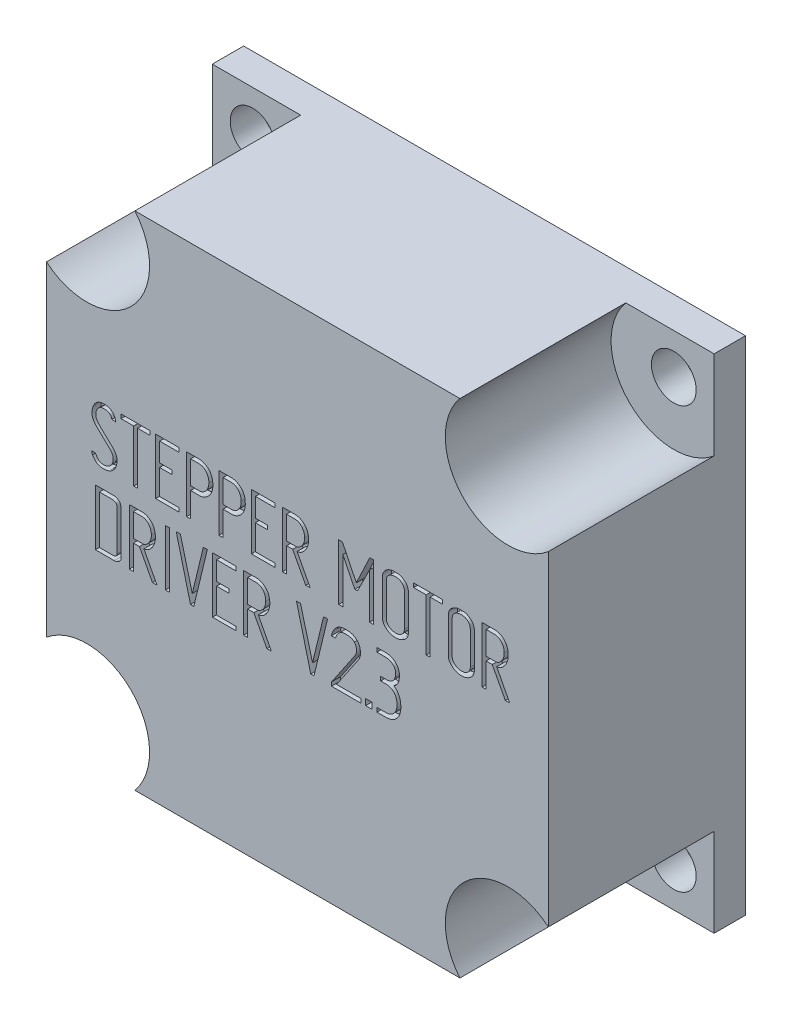
SolidWorks part; units mm, degrees
ref_plane "Front Plane" through (0, 0, 0) normal (0, 0, 1) x (1, 0, 0)
ref_plane "Top Plane" through (0, 0, 0) normal (0, 1, 0) x (1, 0, 0)
ref_plane "Right Plane" through (0, 0, 0) normal (1, 0, 0) x (0, 0, -1)
ref_plane "Plane1" through (0, 0, 22) normal (0, 0, 1) x (1, 0, 0)
sketch "Sketch1" plane through (0, 0, 22) normal (0, 0, 1) x (1, 0, 0)
  line L0 (-22.094, 7.6151) -> (-22.094, -6.9533)
  line L1 (-20.4497, -6.9533) -> (28, -6.9533)
  line L2 (28, -6.9533) -> (28, 7.6151)
  line L3 (28, 7.6151) -> (-22.094, 7.6151)
  line L4 (-11.9113, 4.083) -> (-11.9113, 7.5989)
  line L5 (-8.2986, 4.083) -> (-8.2986, 7.5989)
  line L6 (-0.0334, 4.1265) -> (1.4223, 1.3505)
  line L7 (1.4223, 1.3505) -> (0.9242, 1.3505)
  line L8 (0.9242, 1.3505) -> (-0.5316, 4.0975)
  line L9 (-0.5316, 4.0975) -> (-1.6681, 4.0975)
  line L10 (-1.6681, 4.0975) -> (-1.6681, 7.5989)
  spline S0 degree 3 poles (-20.4497, -6.9533) (-20.9978, -6.9533) (-21.5459, -6.9533) (-22.094, -6.9533) knots 0.061126 0.061126 0.061126 0.061126 0.154392 0.154392 0.154392 0.154392
  spline S1 degree 3 poles (-9.4351, 5.8531) (-9.4351, 6.6849) (-9.7673, 7.2304) (-10.4362, 7.4877) (-10.6248, 7.5603) (-10.7989, 7.5989) (-10.9488, 7.5989) (-11.2696, 7.5989) (-11.5904, 7.5989) (-11.9113, 7.5989) knots 0.764873 0.764873 0.764873 0.764873 0.88574 0.88574 0.88574 0.916733 0.916733 0.916733 0.973286 0.973286 0.973286 0.973286
  spline S2 degree 3 poles (-11.9113, 4.083) (-11.584, 4.083) (-11.2567, 4.0786) (-10.9295, 4.083) (-10.5716, 4.0878) (-10.2488, 4.2344) (-9.9526, 4.5183) (-9.6044, 4.852) (-9.4351, 5.2969) (-9.4351, 5.8531) knots 0 0 0 0 0.057691 0.057691 0.057691 0.122121 0.122121 0.122121 0.208716 0.208716 0.208716 0.208716
  spline S3 degree 3 poles (-5.8176, 5.8531) (-5.8176, 6.6849) (-6.1546, 7.2304) (-6.8235, 7.4877) (-7.0121, 7.5603) (-7.1814, 7.5989) (-7.3362, 7.5989) (-7.657, 7.5989) (-7.9778, 7.5989) (-8.2986, 7.5989) knots 0.764782 0.764782 0.764782 0.764782 0.885765 0.885765 0.885765 0.916754 0.916754 0.916754 0.973293 0.973293 0.973293 0.973293
  spline S4 degree 3 poles (-8.2986, 4.083) (-7.9713, 4.083) (-7.644, 4.0786) (-7.3168, 4.083) (-6.9589, 4.0878) (-6.6361, 4.2344) (-6.3399, 4.5183) (-5.9917, 4.852) (-5.8176, 5.2969) (-5.8176, 5.8531) knots 0 0 0 0 0.057676 0.057676 0.057676 0.12209 0.12209 0.12209 0.208766 0.208766 0.208766 0.208766
  spline S5 degree 3 poles (-0.0334, 4.1265) (0.3438, 4.1797) (0.6607, 4.3892) (0.9097, 4.7601) (1.137, 5.0986) (1.2482, 5.471) (1.2482, 6.6849) (0.9187, 7.2141) (0.2713, 7.4974) (0.1165, 7.5651) (-0.0431, 7.5989) (-0.2075, 7.5989) (-0.6944, 7.5989) (-1.1812, 7.5989) (-1.6681, 7.5989) knots 0.592094 0.592094 0.592094 0.592094 0.642618 0.642618 0.642618 0.688837 0.688837 0.780724 0.780724 0.780724 0.80197 0.80197 0.80197 0.864914 0.864914 0.864914 0.864914
extrude "Boss-Extrude1" add sketch "Sketch1" against normal blind 1
sketch "Sketch2" plane through (-22.094, 0, 0) normal (-1, 0, 0) x (0, 0, 1)
  line L0 (21, 7.6151) -> (22, 7.6151)
  line L1 (22, 7.6151) -> (22, -6.9533)
  line L2 (22, -6.9533) -> (21, -6.9533)
  line L3 (21, -6.9533) -> (21, 7.6151)
extrude "Boss-Extrude2" add sketch "Sketch2" along normal blind 5.906
sketch "Sketch3" plane through (0, 0, 21) normal (0, 0, -1) x (-1, 0, 0)
  line L0 (-28, -6.9533) -> (-28, 7.6151)
  line L1 (-28, 7.6151) -> (28, 7.6151)
  line L2 (28, 7.6151) -> (28, -6.9533)
  line L3 (28, -6.9533) -> (-28, -6.9533)
extrude "Boss-Extrude3" add sketch "Sketch3" along normal blind 21
sketch "Sketch4" plane through (0, 0, 22) normal (0, 0, 1) x (1, 0, 0)
  line L0 (8.8629, -0.6904) -> (8.8629, -1.145)
  line L1 (9.2885, -3.2681) -> (9.2885, -3.7227)
  line L2 (8.8725, -6.4842) -> (8.8725, -6.9388)
  spline S0 degree 3 poles (8.8629, -0.6904) (9.1676, -0.6904) (9.4722, -0.6904) (9.7769, -0.6904) (10.4685, -0.6904) (10.9521, -0.9516) (11.2181, -1.4739) (11.3271, -1.6878) (11.3826, -1.8849) (11.3826, -2.3541) (11.3535, -2.591) (11.3003, -2.77) (11.2167, -3.0515) (11.0295, -3.2826) (10.749, -3.4761) knots 0.699691 0.699691 0.699691 0.699691 0.739881 0.739881 0.739881 0.816228 0.816228 0.816228 0.839159 0.839159 0.874762 0.874762 0.874762 0.914947 0.914947 0.914947 0.914947
  spline S1 degree 3 poles (9.2885, -3.2681) (9.5045, -3.2681) (9.7205, -3.2681) (9.9365, -3.2681) (10.3089, -3.2681) (10.5942, -3.1182) (10.8022, -2.8135) (10.865, -2.7215) (10.9086, -2.6104) (10.928, -2.4895) (10.9374, -2.4306) (10.9473, -2.2912) (10.9473, -1.8076) (10.8216, -1.5754) (10.5701, -1.3917) (10.3499, -1.2307) (10.0961, -1.145) (9.8011, -1.145) (9.4884, -1.145) (9.1756, -1.145) (8.8629, -1.145) knots 0.459525 0.459525 0.459525 0.459525 0.488019 0.488019 0.488019 0.532951 0.532951 0.532951 0.548357 0.548357 0.548357 0.5721 0.5721 0.60232 0.60232 0.60232 0.638466 0.638466 0.638466 0.679703 0.679703 0.679703 0.679703
  spline S2 degree 3 poles (8.8725, -6.4842) (9.1933, -6.4842) (9.5142, -6.4842) (9.835, -6.4842) (10.2219, -6.4842) (10.5362, -6.3488) (10.7732, -6.0828) (11.0035, -5.8243) (11.1166, -5.4976) (11.1166, -4.7142) (11.0198, -4.3901) (10.8264, -4.1386) (10.6159, -3.865) (10.3186, -3.7227) (9.9317, -3.7227) (9.7173, -3.7227) (9.5029, -3.7227) (9.2885, -3.7227) knots 0.185727 0.185727 0.185727 0.185727 0.228043 0.228043 0.228043 0.274363 0.274363 0.274363 0.320276 0.320276 0.366189 0.366189 0.366189 0.411267 0.411267 0.411267 0.439537 0.439537 0.439537 0.439537
  spline S3 degree 3 poles (11.5422, -5.1301) (11.5422, -5.6621) (11.3922, -6.0925) (11.0972, -6.4214) (10.7883, -6.7657) (10.3766, -6.9388) (9.8543, -6.9388) (9.527, -6.9388) (9.1998, -6.9388) (8.8725, -6.9388) knots 0 0 0 0 0.061468 0.061468 0.061468 0.122594 0.122594 0.122594 0.165739 0.165739 0.165739 0.165739
  spline S4 degree 3 poles (10.749, -3.4761) (11.015, -3.5921) (11.223, -3.8243) (11.368, -4.1773) (11.4834, -4.4581) (11.5422, -4.777) (11.5422, -5.1301) knots 0.914947 0.914947 0.914947 0.914947 0.957143 0.957143 0.957143 1 1 1 1
extrude "Cut-Extrude1" cut sketch "Sketch4" against normal blind 1
sketch "Sketch5" plane through (0, 0, 22) normal (0, 0, 1) x (1, 0, 0)
  line L0 (-5.9989, -0.6904) -> (-5.9989, -4.1918)
  line L1 (-5.9989, -4.1918) -> (-4.8624, -4.1918)
  line L2 (-4.8624, -4.1918) -> (-3.4067, -6.9388)
  line L3 (-3.4067, -6.9388) -> (-2.9086, -6.9388)
  line L4 (-2.9086, -6.9388) -> (-4.3691, -4.1628)
  spline S0 degree 3 poles (-5.9989, -0.6904) (-5.5121, -0.6904) (-5.0252, -0.6904) (-4.5384, -0.6904) (-4.3788, -0.6904) (-4.2144, -0.7242) (-4.0596, -0.792) (-3.4121, -1.0752) (-3.0827, -1.6044) (-3.0827, -2.8183) (-3.1939, -3.1907) (-3.4212, -3.5293) (-3.6695, -3.899) (-3.9871, -4.1096) (-4.3691, -4.1628) knots 0.591928 0.591928 0.591928 0.591928 0.654854 0.654854 0.654854 0.67609 0.67609 0.67609 0.767952 0.767952 0.814158 0.814158 0.814158 0.864855 0.864855 0.864855 0.864855
extrude "Cut-Extrude2" cut sketch "Sketch5" against normal blind 1
sketch "Sketch6" plane through (0, 0, 21) normal (0, 0, 1) x (1, 0, 0)
  line L0 (-5.5492, -3.7372) -> (-5.5492, -1.145)
  spline S0 degree 3 poles (-5.5492, -3.7372) (-5.1977, -3.7372) (-4.8463, -3.7372) (-4.4949, -3.7372) (-4.2966, -3.7372) (-4.0983, -3.6308) (-3.9, -3.4132) (-3.6627, -3.1528) (-3.5373, -2.8232) (-3.5373, -2.4169) knots 0.655267 0.655267 0.655267 0.655267 0.783334 0.783334 0.783334 0.868074 0.868074 0.868074 1 1 1 1
  spline S1 degree 3 poles (-3.5373, -2.4169) (-3.5373, -2.0204) (-3.6534, -1.6963) (-3.8903, -1.4497) (-4.087, -1.245) (-4.3159, -1.145) (-4.5722, -1.145) (-4.8979, -1.145) (-5.2235, -1.145) (-5.5492, -1.145) knots 0 0 0 0 0.128337 0.128337 0.128337 0.22169 0.22169 0.22169 0.340387 0.340387 0.340387 0.340387
extrude "Boss-Extrude4" add sketch "Sketch6" along normal blind 1
sketch "Sketch7" plane through (0, 0, 22) normal (0, 0, 1) x (1, 0, 0)
  line L0 (-18.7666, -0.6904) -> (-18.7666, -4.1918)
  line L1 (-18.7666, -4.1918) -> (-17.6301, -4.1918)
  line L2 (-17.6301, -4.1918) -> (-16.1744, -6.9388)
  line L3 (-16.1744, -6.9388) -> (-15.6763, -6.9388)
  line L4 (-15.6763, -6.9388) -> (-17.132, -4.1628)
  spline S0 degree 3 poles (-18.7666, -0.6904) (-18.2798, -0.6904) (-17.7929, -0.6904) (-17.3061, -0.6904) (-17.1417, -0.6904) (-16.9821, -0.7242) (-16.8225, -0.792) (-16.1759, -1.0663) (-15.8504, -1.6044) (-15.8504, -2.8183) (-15.9616, -3.1907) (-16.1889, -3.5293) (-16.4357, -3.8968) (-16.7499, -4.1096) (-17.132, -4.1628) knots 0.591995 0.591995 0.591995 0.591995 0.654928 0.654928 0.654928 0.676368 0.676368 0.676368 0.768214 0.768214 0.814412 0.814412 0.814412 0.864937 0.864937 0.864937 0.864937
extrude "Cut-Extrude3" cut sketch "Sketch7" against normal blind 1
sketch "Sketch8" plane through (0, 0, 21) normal (0, 0, 1) x (1, 0, 0)
  line L0 (-18.312, -3.7372) -> (-18.312, -1.145)
  spline S0 degree 3 poles (-18.312, -3.7372) (-17.9606, -3.7372) (-17.6092, -3.7372) (-17.2577, -3.7372) (-17.0643, -3.7372) (-16.866, -3.6308) (-16.6677, -3.4132) (-16.4282, -3.1504) (-16.3002, -2.8232) (-16.3002, -2.4169) knots 0.655365 0.655365 0.655365 0.655365 0.78352 0.78352 0.78352 0.867758 0.867758 0.867758 1 1 1 1
  spline S1 degree 3 poles (-16.3002, -2.4169) (-16.3002, -2.0204) (-16.4211, -1.6963) (-16.658, -1.4497) (-16.8524, -1.2474) (-17.0788, -1.145) (-17.3351, -1.145) (-17.6608, -1.145) (-17.9864, -1.145) (-18.312, -1.145) knots 0 0 0 0 0.128628 0.128628 0.128628 0.221536 0.221536 0.221536 0.340269 0.340269 0.340269 0.340269
extrude "Boss-Extrude5" add sketch "Sketch8" along normal blind 1
sketch "Sketch9" plane through (0, 0, 22) normal (0, 0, 1) x (1, 0, 0)
  line L0 (-22.094, -6.5132) -> (-22.094, -6.9533)
  line L1 (-22.094, -0.6904) -> (-22.094, -1.145)
  spline S0 degree 3 poles (-20.4497, -6.9533) (-20.9978, -6.9533) (-21.5459, -6.9533) (-22.094, -6.9533) knots 0.061126 0.061126 0.061126 0.061126 0.154392 0.154392 0.154392 0.154392
  spline S1 degree 3 poles (-19.6855, -6.3488) (-19.6855, -6.5326) (-19.7726, -6.6777) (-19.9419, -6.7937) (-20.0935, -6.8977) (-20.261, -6.9533) (-20.4497, -6.9533) knots 0 0 0 0 0.03043 0.03043 0.03043 0.061126 0.061126 0.061126 0.061126
  spline S2 degree 3 poles (-20.2562, -0.7339) (-19.879, -0.8355) (-19.6855, -1.087) (-19.6855, -1.4932) (-19.6855, -3.1117) (-19.6855, -4.7303) (-19.6855, -6.3488) knots 0.665783 0.665783 0.665783 0.665783 0.724543 0.724543 0.724543 1 1 1 1
  spline S3 degree 3 poles (-22.094, -0.6904) (-21.6168, -0.6904) (-21.1396, -0.6904) (-20.6625, -0.6904) (-20.4497, -0.6904) (-20.3142, -0.7049) (-20.2562, -0.7339) knots 0.561263 0.561263 0.561263 0.561263 0.642474 0.642474 0.642474 0.665783 0.665783 0.665783 0.665783
  spline S4 degree 3 poles (-20.1401, -6.1554) (-20.1401, -4.6497) (-20.1401, -3.144) (-20.1401, -1.6383) (-20.1401, -1.3094) (-20.3142, -1.145) (-20.6673, -1.145) (-21.1429, -1.145) (-21.6184, -1.145) (-22.094, -1.145) knots 0 0 0 0 0.315993 0.315993 0.315993 0.37397 0.37397 0.37397 0.473775 0.473775 0.473775 0.473775
  spline S5 degree 3 poles (-22.094, -6.5132) (-21.6104, -6.5132) (-21.1267, -6.5132) (-20.6431, -6.5132) (-20.3094, -6.5132) (-20.1401, -6.3972) (-20.1401, -6.1554) knots 0.849313 0.849313 0.849313 0.849313 0.95081 0.95081 0.95081 1 1 1 1
extrude "Cut-Extrude4" cut sketch "Sketch9" against normal blind 1
sketch "Sketch10" plane through (0, 0, 22) normal (0, 0, 1) x (1, 0, 0)
  line L0 (20.6029, 7.5989) -> (20.6029, 4.0975)
  line L1 (20.6029, 4.0975) -> (21.7394, 4.0975)
  line L2 (21.7394, 4.0975) -> (23.1999, 1.3505)
  line L3 (23.1999, 1.3505) -> (23.6932, 1.3505)
  line L4 (23.6932, 1.3505) -> (22.2375, 4.1265)
  spline S0 degree 3 poles (20.6029, 7.5989) (21.0913, 7.5989) (21.5798, 7.5989) (22.0683, 7.5989) (22.2279, 7.5989) (22.3875, 7.5651) (22.547, 7.4974) (23.1977, 7.2213) (23.524, 6.6849) (23.524, 5.471) (23.4079, 5.0986) (23.1854, 4.7601) (22.9387, 4.3846) (22.6196, 4.1797) (22.2375, 4.1265) knots 0.591753 0.591753 0.591753 0.591753 0.65488 0.65488 0.65488 0.676109 0.676109 0.676109 0.768003 0.768003 0.814226 0.814226 0.814226 0.864967 0.864967 0.864967 0.864967
extrude "Cut-Extrude5" cut sketch "Sketch10" against normal blind 1
sketch "Sketch11" plane through (0, 0, 21) normal (0, 0, 1) x (1, 0, 0)
  line L0 (21.0575, 4.5521) -> (21.0575, 7.1443)
  spline S0 degree 3 poles (21.0575, 4.5521) (21.4089, 4.5521) (21.7604, 4.5521) (22.1118, 4.5521) (22.3052, 4.5521) (22.5035, 4.6585) (22.7066, 4.8761) (22.9471, 5.1337) (23.0694, 5.4662) (23.0694, 5.8724) knots 0.655176 0.655176 0.655176 0.655176 0.783281 0.783281 0.783281 0.867942 0.867942 0.867942 1 1 1 1
  spline S1 degree 3 poles (23.0694, 5.8724) (23.0694, 6.269) (22.9533, 6.5882) (22.7163, 6.8348) (22.5172, 7.042) (22.2907, 7.1443) (22.0344, 7.1443) (21.7088, 7.1443) (21.3831, 7.1443) (21.0575, 7.1443) knots 0 0 0 0 0.127832 0.127832 0.127832 0.221516 0.221516 0.221516 0.340204 0.340204 0.340204 0.340204
extrude "Boss-Extrude6" add sketch "Sketch11" along normal blind 1
sketch "Sketch12" plane through (0, 0, 22) normal (0, 0, 1) x (1, 0, 0)
  line L0 (18.625, 7.6151) -> (17.9743, 7.6151)
  spline S0 degree 3 poles (18.625, 7.6151) (18.8668, 7.5692) (19.0854, 7.4665) (19.2826, 7.3136) (19.5875, 7.077) (19.742, 6.7768) (19.742, 6.4189) (19.742, 5.1163) (19.742, 3.8138) (19.742, 2.5112) (19.742, 2.1485) (19.5873, 1.8486) (19.2826, 1.6165) (19.0002, 1.4013) (18.678, 1.2925) (17.9333, 1.2925) (17.6044, 1.3989) (17.3142, 1.6213) (16.9964, 1.865) (16.8354, 2.163) (16.8354, 2.5209) (16.8354, 3.8202) (16.8354, 5.1196) (16.8354, 6.4189) (16.8354, 6.8106) (16.9999, 7.125) (17.3239, 7.3571) (17.5103, 7.4907) (17.7263, 7.5751) (17.9743, 7.6151) knots 0.65 0.65 0.65 0.65 0.695442 0.695442 0.695442 0.759666 0.759666 0.759666 1 1 1 1.064284 1.064284 1.064284 1.12926 1.12926 1.194235 1.194235 1.194235 1.259381 1.259381 1.259381 1.499095 1.499095 1.499095 1.566888 1.566888 1.566888 1.611816 1.611816 1.611816 1.611816
extrude "Cut-Extrude6" cut sketch "Sketch12" against normal blind 1
sketch "Sketch13" plane through (0, 0, 22) normal (0, 0, 1) x (1, 0, 0)
  line L0 (11.2693, 7.6151) -> (10.6205, 7.6151)
  spline S0 degree 3 poles (11.2693, 7.6151) (11.5113, 7.5692) (11.731, 7.4665) (11.9315, 7.3136) (12.2384, 7.0795) (12.3861, 6.7768) (12.3861, 6.4189) (12.3861, 5.1163) (12.3861, 3.8138) (12.3861, 2.5112) (12.3861, 2.1485) (12.2362, 1.8486) (11.9315, 1.6165) (11.646, 1.399) (11.3221, 1.2925) (10.5822, 1.2925) (10.2485, 1.3989) (9.9583, 1.6213) (9.6435, 1.8626) (9.4843, 2.163) (9.4843, 2.5209) (9.4843, 3.8202) (9.4843, 5.1196) (9.4843, 6.4189) (9.4843, 6.8106) (9.6439, 7.125) (9.968, 7.3571) (10.1543, 7.4907) (10.3727, 7.5751) (10.6205, 7.6151) knots 0.649922 0.649922 0.649922 0.649922 0.695537 0.695537 0.695537 0.759638 0.759638 0.759638 1 1 1 1.064152 1.064152 1.064152 1.12969 1.12969 1.194377 1.194377 1.194377 1.259336 1.259336 1.259336 1.499071 1.499071 1.499071 1.566736 1.566736 1.566736 1.611656 1.611656 1.611656 1.611656
extrude "Cut-Extrude7" cut sketch "Sketch13" against normal blind 1
sketch "Sketch14" plane through (0, 0, 21) normal (0, 0, 1) x (1, 0, 0)
  spline S0 degree 3 poles (9.9196, 6.3318) (9.9196, 5.0873) (9.9196, 3.8428) (9.9196, 2.5983) (9.9196, 2.3323) (10.0502, 2.1146) (10.3162, 1.9502) (10.5272, 1.8197) (10.7466, 1.7471) (11.2012, 1.7471) (11.414, 1.8099) (11.6026, 1.9454) (11.8227, 2.1034) (11.9315, 2.3178) (11.9315, 2.5983) knots 0.500978 0.500978 0.500978 0.500978 0.780719 0.780719 0.780719 0.840435 0.840435 0.840435 0.890577 0.890577 0.942898 0.942898 0.942898 1 1 1 1
  spline S1 degree 3 poles (11.9315, 2.5983) (11.9315, 3.8412) (11.9315, 5.0841) (11.9315, 6.327) (11.9315, 6.5833) (11.8347, 6.7961) (11.6413, 6.9557) (11.456, 7.1086) (11.2351, 7.1879) (10.7224, 7.1879) (10.5048, 7.1298) (10.3162, 7.0186) (10.0526, 6.8631) (9.9196, 6.6317) (9.9196, 6.3318) knots 0 0 0 0 0.279319 0.279319 0.279319 0.333033 0.333033 0.333033 0.387798 0.387798 0.43858 0.43858 0.43858 0.500978 0.500978 0.500978 0.500978
extrude "Boss-Extrude7" add sketch "Sketch14" along normal blind 1
sketch "Sketch15" plane through (0, 0, 22) normal (0, 0, 1) x (1, 0, 0)
  line L0 (-20.7132, 6.5495) -> (-20.2635, 6.5495)
  line L1 (-20.2635, 6.5495) -> (-20.336, 6.83)
  line L2 (-22.551, 2.4) -> (-22.9766, 2.4)
  line L3 (-22.9766, 2.4) -> (-22.8654, 2.0518)
  spline S0 degree 3 poles (-20.128, 2.8884) (-20.128, 3.2705) (-20.3383, 3.6502) (-20.7471, 4.0346) (-21.1259, 4.3909) (-21.5048, 4.7472) (-21.8836, 5.1034) (-22.2899, 5.4855) (-22.4978, 5.8144) (-22.4978, 6.3899) (-22.4282, 6.6475) (-22.2753, 6.8397) (-22.1061, 7.0524) (-21.8739, 7.1588) (-21.0711, 7.1588) (-20.7809, 6.9557) (-20.7132, 6.5495) knots 0.706165 0.706165 0.706165 0.706165 0.763602 0.763602 0.763602 0.830481 0.830481 0.830481 0.869878 0.869878 0.91572 0.91572 0.91572 0.946691 0.946691 1 1 1 1
  spline S1 degree 3 poles (-20.336, 6.83) (-20.5391, 7.3523) (-20.955, 7.6135) (-22.0239, 7.6135) (-22.3638, 7.4549) (-22.5994, 7.1443) (-22.8122, 6.8638) (-22.9234, 6.4963) (-22.9234, 5.6741) (-22.7213, 5.3007) (-22.314, 4.9197) (-21.9384, 4.5682) (-21.5701, 4.2087) (-21.1872, 3.8654) (-20.7664, 3.4881) (-20.5536, 3.1448) (-20.5536, 2.5064) (-20.6601, 2.2451) (-20.8632, 2.0324) (-21.0663, 1.8196) (-21.3274, 1.7181) (-21.9078, 1.7181) (-22.1143, 1.7923) (-22.2608, 1.9502) (-22.3237, 2.0179) (-22.4204, 2.1678) (-22.551, 2.4) knots 0.203882 0.203882 0.203882 0.203882 0.273058 0.273058 0.321481 0.321481 0.321481 0.379716 0.379716 0.427932 0.427932 0.427932 0.494085 0.494085 0.494085 0.539652 0.539652 0.585219 0.585219 0.585219 0.621664 0.621664 0.651483 0.651483 0.651483 0.674464 0.674464 0.674464 0.674464
  spline S2 degree 3 poles (-22.8654, 2.0518) (-22.6719, 1.7858) (-22.541, 1.6266) (-22.4688, 1.5681) (-22.2657, 1.4037) (-21.9948, 1.3215) (-21.1824, 1.3215) (-20.8101, 1.4667) (-20.5391, 1.7519) (-20.2635, 2.0421) (-20.128, 2.4193) (-20.128, 2.8884) knots 0 0 0 0 0.026856 0.026856 0.026856 0.064877 0.064877 0.116822 0.116822 0.116822 0.169968 0.169968 0.169968 0.169968
extrude "Cut-Extrude8" cut sketch "Sketch15" against normal blind 1
sketch "Sketch16" plane through (-8.2986, 0, 0) normal (1, 0, 0) x (0, 0, -1)
  line L0 (-22, 4.083) -> (-21, 4.083)
  line L1 (-21, 4.083) -> (-21, 7.5989)
  line L2 (-21, 7.5989) -> (-22, 7.5989)
  line L3 (-22, 7.5989) -> (-22, 4.083)
extrude "Cut-Extrude9" cut sketch "Sketch16" against normal blind 0.4546
sketch "Sketch17" plane through (-11.9113, 0, 0) normal (1, 0, 0) x (0, 0, -1)
  line L0 (-22, 4.083) -> (-21, 4.083)
  line L1 (-21, 4.083) -> (-21, 7.5989)
  line L2 (-21, 7.5989) -> (-22, 7.5989)
  line L3 (-22, 7.5989) -> (-22, 4.083)
extrude "Cut-Extrude10" cut sketch "Sketch17" against normal blind 0.4546
sketch "Sketch18" plane through (-22.094, 0, 0) normal (1, 0, 0) x (0, 0, -1)
  line L0 (-22, -0.6904) -> (-22, -6.9533)
  line L1 (-22, -6.9533) -> (-21, -6.9533)
  line L2 (-21, -6.9533) -> (-21, -0.6904)
  line L3 (-21, -0.6904) -> (-22, -0.6904)
extrude "Cut-Extrude11" cut sketch "Sketch18" against normal blind 0.4546
sketch "Sketch19" plane through (0, -6.9533, 0) normal (0, -1, 0) x (1, 0, 0)
  line L0 (28, 22) -> (28, 0)
  line L1 (28, 0) -> (-28, 0)
  line L2 (-28, 0) -> (-28, 22)
  line L3 (-28, 22) -> (28, 22)
extrude "Boss-Extrude8" add sketch "Sketch19" along normal blind 21.0467
sketch "Sketch20" plane through (0, 7.6151, 0) normal (0, 1, 0) x (-1, 0, 0)
  line L0 (28, 22) -> (28, 0)
  line L1 (28, 0) -> (-28, 0)
  line L2 (-28, 0) -> (-28, 22)
  line L3 (-28, 22) -> (28, 22)
extrude "Boss-Extrude9" add sketch "Sketch20" along normal blind 20.3849
sketch "Sketch21" plane through (0, 4.083, 0) normal (0, 1, 0) x (-1, 0, 0)
  line L0 (8.7532, 22) -> (8.2986, 22)
  line L1 (8.2986, 22) -> (8.2986, 21)
  line L2 (8.2986, 21) -> (8.7532, 21)
  line L3 (8.7532, 21) -> (8.7532, 22)
extrude "Cut-Extrude12" cut sketch "Sketch21" against normal blind 2.747
sketch "Sketch22" plane through (0, 4.0975, 0) normal (0, 1, 0) x (-1, 0, 0)
  line L0 (1.6681, 22) -> (1.2135, 22)
  line L1 (1.2135, 22) -> (1.2135, 21)
  line L2 (1.2135, 21) -> (1.6681, 21)
  line L3 (1.6681, 21) -> (1.6681, 22)
extrude "Cut-Extrude13" cut sketch "Sketch22" against normal blind 2.747
sketch "Sketch23" plane through (0, 4.0975, 0) normal (0, 1, 0) x (-1, 0, 0)
  line L0 (-20.6029, 22) -> (-21.0575, 22)
  line L1 (-21.0575, 22) -> (-21.0575, 21)
  line L2 (-21.0575, 21) -> (-20.6029, 21)
  line L3 (-20.6029, 21) -> (-20.6029, 22)
extrude "Cut-Extrude14" cut sketch "Sketch23" against normal blind 2.747
sketch "Sketch24" plane through (0, -4.1918, 0) normal (0, 1, 0) x (-1, 0, 0)
  line L0 (18.7666, 22) -> (18.312, 22)
  line L1 (18.312, 22) -> (18.312, 21)
  line L2 (18.312, 21) -> (18.7666, 21)
  line L3 (18.7666, 21) -> (18.7666, 22)
extrude "Cut-Extrude15" cut sketch "Sketch24" against normal blind 2.747
sketch "Sketch25" plane through (0, -4.1918, 0) normal (0, 1, 0) x (-1, 0, 0)
  line L0 (5.9989, 22) -> (5.5492, 22)
  line L1 (5.5492, 22) -> (5.5492, 21)
  line L2 (5.5492, 21) -> (5.9989, 21)
  line L3 (5.9989, 21) -> (5.9989, 22)
extrude "Cut-Extrude16" cut sketch "Sketch25" against normal blind 2.747
sketch "Sketch26" plane through (0, 4.083, 0) normal (0, 1, 0) x (-1, 0, 0)
  line L0 (12.3659, 22) -> (11.9113, 22)
  line L1 (11.9113, 22) -> (11.9113, 21)
  line L2 (11.9113, 21) -> (12.3659, 21)
  line L3 (12.3659, 21) -> (12.3659, 22)
extrude "Cut-Extrude17" cut sketch "Sketch26" against normal blind 2.747
sketch "Sketch27" plane through (0, 0, 21) normal (0, 0, 1) x (1, 0, 0)
  line L0 (-1.2135, 4.5521) -> (-1.2135, 7.1443)
  spline S0 degree 3 poles (-1.2135, 7.1443) (-0.8894, 7.1443) (-0.5654, 7.1443) (-0.2414, 7.1443) (0.0198, 7.1443) (0.2438, 7.0396) (0.4405, 6.8348) (0.6775, 6.5882) (0.7984, 6.269) (0.7984, 5.8724) knots 0 0 0 0 0.118137 0.118137 0.118137 0.211946 0.211946 0.211946 0.340071 0.340071 0.340071 0.340071
  spline S1 degree 3 poles (0.7984, 5.8724) (0.7984, 5.4662) (0.6703, 5.139) (0.4309, 4.8761) (0.2326, 4.6585) (0.0343, 4.5521) (-0.1592, 4.5521) (-0.5106, 4.5521) (-0.862, 4.5521) (-1.2135, 4.5521) knots 0.655262 0.655262 0.655262 0.655262 0.787543 0.787543 0.787543 0.871807 0.871807 0.871807 1 1 1 1
extrude "Boss-Extrude10" add sketch "Sketch27" along normal blind 1
sketch "Sketch28" plane through (0, 0, 21) normal (0, 0, 1) x (1, 0, 0)
  line L0 (-8.2986, 4.5376) -> (-8.2986, 7.1443)
  spline S0 degree 3 poles (-6.2722, 5.8579) (-6.2722, 5.4468) (-6.3987, 5.1139) (-6.6397, 4.8616) (-6.8477, 4.644) (-7.075, 4.5376) (-7.3265, 4.5376) (-7.6505, 4.5376) (-7.9745, 4.5376) (-8.2986, 4.5376) knots 0.655969 0.655969 0.655969 0.655969 0.78778 0.78778 0.78778 0.882375 0.882375 0.882375 1 1 1 1
  spline S1 degree 3 poles (-8.2986, 7.1443) (-7.9891, 7.1443) (-7.6795, 7.1443) (-7.37, 7.1443) (-7.0363, 7.1443) (-6.7689, 7.0062) (-6.5624, 6.7429) (-6.3689, 6.4963) (-6.2722, 6.2013) (-6.2722, 5.8579) knots 0 0 0 0 0.112302 0.112302 0.112302 0.225653 0.225653 0.225653 0.340548 0.340548 0.340548 0.340548
extrude "Boss-Extrude11" add sketch "Sketch28" along normal blind 1
sketch "Sketch29" plane through (0, 0, 21) normal (0, 0, 1) x (1, 0, 0)
  line L0 (-11.9113, 4.5376) -> (-11.9113, 7.1443)
  spline S0 degree 3 poles (-9.8849, 5.8579) (-9.8849, 5.4468) (-10.0114, 5.1139) (-10.2524, 4.8616) (-10.4604, 4.644) (-10.6877, 4.5376) (-10.9392, 4.5376) (-11.2632, 4.5376) (-11.5872, 4.5376) (-11.9113, 4.5376) knots 0.655969 0.655969 0.655969 0.655969 0.78778 0.78778 0.78778 0.882375 0.882375 0.882375 1 1 1 1
  spline S1 degree 3 poles (-11.9113, 7.1443) (-11.6017, 7.1443) (-11.2922, 7.1443) (-10.9827, 7.1443) (-10.649, 7.1443) (-10.3816, 7.0062) (-10.175, 6.7429) (-9.9816, 6.4963) (-9.8849, 6.2013) (-9.8849, 5.8579) knots 0 0 0 0 0.112302 0.112302 0.112302 0.225653 0.225653 0.225653 0.340548 0.340548 0.340548 0.340548
extrude "Boss-Extrude12" add sketch "Sketch29" along normal blind 1
sketch "Sketch30" plane through (0, 0, 21) normal (0, 0, 1) x (1, 0, 0)
  spline S0 degree 3 poles (17.2755, 6.3318) (17.2755, 5.0873) (17.2755, 3.8428) (17.2755, 2.5983) (17.2755, 2.3323) (17.4061, 2.1146) (17.6673, 1.9502) (17.8807, 1.8158) (18.0977, 1.7471) (18.5523, 1.7471) (18.7651, 1.8099) (18.9537, 1.9454) (19.1738, 2.1034) (19.2874, 2.3178) (19.2874, 2.5983) knots 0.501005 0.501005 0.501005 0.501005 0.780742 0.780742 0.780742 0.840205 0.840205 0.840205 0.891464 0.891464 0.942723 0.942723 0.942723 1 1 1 1
  spline S1 degree 3 poles (19.2874, 2.5983) (19.2874, 3.8412) (19.2874, 5.0841) (19.2874, 6.327) (19.2874, 6.5833) (19.1907, 6.7961) (18.9924, 6.9557) (18.8082, 7.104) (18.5862, 7.1879) (18.0735, 7.1879) (17.8559, 7.1298) (17.6721, 7.0186) (17.4067, 6.858) (17.2755, 6.6317) (17.2755, 6.3318) knots 0 0 0 0 0.279389 0.279389 0.279389 0.333337 0.333337 0.333337 0.386927 0.386927 0.438533 0.438533 0.438533 0.501005 0.501005 0.501005 0.501005
extrude "Boss-Extrude13" add sketch "Sketch30" along normal blind 1
sketch "Sketch31" plane through (0, 0, 22) normal (0, 0, 1) x (1, 0, 0)
  line L0 (8.0528, 1.336) -> (8.5026, 1.336)
  line L1 (8.5026, 1.336) -> (8.5026, 7.5989)
  line L2 (8.5026, 7.5989) -> (8.077, 7.5893)
  line L3 (8.077, 7.5893) -> (6.5729, 4.407)
  line L4 (6.5729, 4.407) -> (5.0205, 7.5893)
  line L5 (5.0205, 7.5893) -> (4.6094, 7.5989)
  line L6 (4.6094, 7.5989) -> (4.6094, 1.336)
  line L7 (4.6094, 1.336) -> (5.064, 1.336)
  line L8 (5.064, 1.336) -> (5.064, 6.3899)
  line L9 (5.064, 6.3899) -> (6.5558, 3.39)
  line L10 (6.5558, 3.39) -> (8.0528, 6.3947)
  line L11 (8.0528, 6.3947) -> (8.0528, 1.336)
extrude "Cut-Extrude18" cut sketch "Sketch31" against normal blind 1
sketch "Sketch32" plane through (0, 0, 22) normal (0, 0, 1) x (1, 0, 0)
  line L0 (-6.8356, -6.9388) -> (-6.8356, -6.5132)
  line L1 (-6.8356, -6.5132) -> (-9.0168, -6.5132)
  line L2 (-9.0168, -6.5132) -> (-9.0168, -3.7082)
  line L3 (-9.0168, -3.7082) -> (-7.6578, -3.7082)
  line L4 (-7.6578, -3.7082) -> (-7.6578, -3.2681)
  line L5 (-7.6578, -3.2681) -> (-9.0168, -3.2681)
  line L6 (-9.0168, -3.2681) -> (-9.0168, -1.1595)
  line L7 (-9.0168, -1.1595) -> (-6.8356, -1.1595)
  line L8 (-6.8356, -1.1595) -> (-6.8356, -0.7049)
  line L9 (-6.8356, -0.7049) -> (-9.4714, -0.7049)
  line L10 (-9.4714, -0.7049) -> (-9.4714, -6.9388)
  line L11 (-9.4714, -6.9388) -> (-6.8356, -6.9388)
extrude "Cut-Extrude19" cut sketch "Sketch32" against normal blind 1
sketch "Sketch33" plane through (0, 0, 22) normal (0, 0, 1) x (1, 0, 0)
  line L0 (-5.1405, 1.3505) -> (-2.5047, 1.3505)
  line L1 (-2.5047, 1.3505) -> (-2.5047, 1.7761)
  line L2 (-2.5047, 1.7761) -> (-4.6859, 1.7761)
  line L3 (-4.6859, 1.7761) -> (-4.6859, 4.5811)
  line L4 (-4.6859, 4.5811) -> (-3.3269, 4.5811)
  line L5 (-3.3269, 4.5811) -> (-3.3269, 5.0212)
  line L6 (-3.3269, 5.0212) -> (-4.6859, 5.0212)
  line L7 (-4.6859, 5.0212) -> (-4.6859, 7.1298)
  line L8 (-4.6859, 7.1298) -> (-2.5047, 7.1298)
  line L9 (-2.5047, 7.1298) -> (-2.5047, 7.5844)
  line L10 (-2.5047, 7.5844) -> (-5.1405, 7.5844)
  line L11 (-5.1405, 7.5844) -> (-5.1405, 1.3505)
extrude "Cut-Extrude20" cut sketch "Sketch33" against normal blind 1
sketch "Sketch34" plane through (0, 0, 22) normal (0, 0, 1) x (1, 0, 0)
  line L0 (-15.8238, 1.3505) -> (-13.188, 1.3505)
  line L1 (-13.188, 1.3505) -> (-13.188, 1.7761)
  line L2 (-13.188, 1.7761) -> (-15.3692, 1.7761)
  line L3 (-15.3692, 1.7761) -> (-15.3692, 4.5811)
  line L4 (-15.3692, 4.5811) -> (-14.0102, 4.5811)
  line L5 (-14.0102, 4.5811) -> (-14.0102, 5.0212)
  line L6 (-14.0102, 5.0212) -> (-15.3692, 5.0212)
  line L7 (-15.3692, 5.0212) -> (-15.3692, 7.1298)
  line L8 (-15.3692, 7.1298) -> (-13.188, 7.1298)
  line L9 (-13.188, 7.1298) -> (-13.188, 7.5844)
  line L10 (-13.188, 7.5844) -> (-15.8238, 7.5844)
  line L11 (-15.8238, 7.5844) -> (-15.8238, 1.3505)
extrude "Cut-Extrude21" cut sketch "Sketch34" against normal blind 1
sketch "Sketch35" plane through (0, 0, 22) normal (0, 0, 1) x (1, 0, 0)
  line L0 (7.0783, -6.9679) -> (7.0783, -6.5132)
  line L1 (7.0783, -6.5132) -> (4.3652, -6.5132)
  line L2 (4.3652, -6.5132) -> (6.8607, -2.8474)
  line L3 (3.7896, -2.1074) -> (4.2394, -2.1074)
  line L4 (3.8235, -6.5326) -> (3.8041, -6.9679)
  line L5 (3.8041, -6.9679) -> (7.0783, -6.9679)
  spline S0 degree 3 poles (3.7896, -2.1074) (4.0073, -1.1547) (4.5393, -0.6759) (5.8982, -0.6759) (6.2948, -0.7968) (6.5802, -1.0386) (6.8839, -1.296) (7.0348, -1.6673) (7.0348, -2.4121) (6.9767, -2.6442) (6.8607, -2.8474) knots 0.492754 0.492754 0.492754 0.492754 0.580033 0.580033 0.632103 0.632103 0.632103 0.681734 0.681734 0.707779 0.707779 0.707779 0.707779
  spline S1 degree 3 poles (6.3577, -1.4255) (6.2706, -1.3578) (6.1981, -1.3094) (6.1352, -1.2804) (5.9251, -1.1835) (5.6806, -1.1305) (4.8198, -1.1305) (4.4329, -1.4545) (4.2394, -2.1074) knots 0.372857 0.372857 0.372857 0.372857 0.383086 0.383086 0.383086 0.413706 0.413706 0.475465 0.475465 0.475465 0.475465
  spline S2 degree 3 poles (3.8235, -6.5326) (4.6779, -5.2735) (5.5323, -4.0145) (6.3867, -2.7555) (6.5276, -2.5479) (6.5947, -2.3299) (6.5947, -1.9333) (6.556, -1.7689) (6.4738, -1.6141) (6.4392, -1.5491) (6.3964, -1.4884) (6.3577, -1.4255) knots 0.142599 0.142599 0.142599 0.142599 0.318057 0.318057 0.318057 0.345151 0.345151 0.364342 0.364342 0.364342 0.372857 0.372857 0.372857 0.372857
extrude "Cut-Extrude22" cut sketch "Sketch35" against normal blind 1
sketch "Sketch36" plane through (0, 0, 22) normal (0, 0, 1) x (1, 0, 0)
  line L0 (16.1825, 7.1443) -> (16.1825, 7.5989)
  line L1 (16.1825, 7.5989) -> (12.9664, 7.5989)
  line L2 (12.9664, 7.5989) -> (12.9664, 7.1443)
  line L3 (12.9664, 7.1443) -> (14.3689, 7.1443)
  line L4 (14.3689, 7.1443) -> (14.3689, 1.336)
  line L5 (14.3689, 1.336) -> (14.809, 1.336)
  line L6 (14.809, 1.336) -> (14.809, 7.1443)
  line L7 (14.809, 7.1443) -> (16.1825, 7.1443)
extrude "Cut-Extrude23" cut sketch "Sketch36" against normal blind 1
sketch "Sketch37" plane through (0, 0, 22) normal (0, 0, 1) x (1, 0, 0)
  line L0 (-17.8357, 7.1443) -> (-16.4622, 7.1443)
  line L1 (-16.4622, 7.1443) -> (-16.4622, 7.5989)
  line L2 (-16.4622, 7.5989) -> (-19.6783, 7.5989)
  line L3 (-19.6783, 7.5989) -> (-19.6783, 7.1443)
  line L4 (-19.6783, 7.1443) -> (-18.2758, 7.1443)
  line L5 (-18.2758, 7.1443) -> (-18.2758, 1.336)
  line L6 (-18.2758, 1.336) -> (-17.8357, 1.336)
  line L7 (-17.8357, 1.336) -> (-17.8357, 7.1443)
extrude "Cut-Extrude24" cut sketch "Sketch37" against normal blind 1
sketch "Sketch38" plane through (0, 0, 22) normal (0, 0, 1) x (1, 0, 0)
  line L0 (3.3641, -0.6904) -> (2.9143, -0.6904)
  line L1 (2.9143, -0.6904) -> (1.6859, -5.7685)
  line L2 (1.6859, -5.7685) -> (0.3462, -0.6904)
  line L3 (0.3462, -0.6904) -> (-0.1084, -0.6904)
  line L4 (-0.1084, -0.6904) -> (1.4876, -6.9388)
  line L5 (1.4876, -6.9388) -> (1.8503, -6.9388)
  line L6 (1.8503, -6.9388) -> (3.3641, -0.6904)
extrude "Cut-Extrude25" cut sketch "Sketch38" against normal blind 1
sketch "Sketch39" plane through (0, 0, 22) normal (0, 0, 1) x (1, 0, 0)
  line L0 (-10.0517, -0.6904) -> (-10.5015, -0.6904)
  line L1 (-10.5015, -0.6904) -> (-11.7347, -5.7685)
  line L2 (-11.7347, -5.7685) -> (-13.0695, -0.6904)
  line L3 (-13.0695, -0.6904) -> (-13.5241, -0.6904)
  line L4 (-13.5241, -0.6904) -> (-11.933, -6.9388)
  line L5 (-11.933, -6.9388) -> (-11.5655, -6.9388)
  line L6 (-11.5655, -6.9388) -> (-10.0517, -0.6904)
extrude "Cut-Extrude26" cut sketch "Sketch39" against normal blind 1
sketch "Sketch40" plane through (0, 0, 22) normal (0, 0, 1) x (1, 0, 0)
  line L0 (8.297, -6.9388) -> (8.297, -6.2569)
  line L1 (8.297, -6.2569) -> (7.6151, -6.2569)
  line L2 (7.6151, -6.2569) -> (7.6151, -6.9388)
  line L3 (7.6151, -6.9388) -> (8.297, -6.9388)
extrude "Cut-Extrude27" cut sketch "Sketch40" against normal blind 1
sketch "Sketch41" plane through (0, 0, 22) normal (0, 0, 1) x (1, 0, 0)
  line L0 (-14.2738, -6.9388) -> (-14.2738, -0.7049)
  line L1 (-14.2738, -0.7049) -> (-14.7284, -0.7049)
  line L2 (-14.7284, -0.7049) -> (-14.7284, -6.9388)
  line L3 (-14.7284, -6.9388) -> (-14.2738, -6.9388)
extrude "Cut-Extrude28" cut sketch "Sketch41" against normal blind 1
hole_wizard "Hole1" positions "Sketch43" profile "Sketch42" legacy
sketch "Sketch43" plane through (0, 0, 22) normal (0, 0, 1) x (1, 0, 0)
  point P0 (-23.5, 23.5)
sketch "Sketch42" plane through (-23.5, 23.5, 22) normal (1, 0, 0) x (0, -1, 0)
  line L0 (0, 0) -> (0, 22)
  line L1 (0, 22) -> (2.5, 22)
  line L2 (2.5, 22) -> (2.5, 18.5)
  line L3 (2.5, 18.5) -> (7, 18.5)
  line L4 (7, 18.5) -> (7, 0)
  line L5 (7, 0) -> (0, 0)
  line L6 (0, 110) -> (0, -10) construction
  dimension "Diameter" = 5
  dimension "Depth" = 22
  dimension "C-Bore Diameter" = 14
  dimension "C-Bore Depth" = 18.5
hole_wizard "Hole2" positions "Sketch45" profile "Sketch44" legacy
sketch "Sketch45" plane through (0, 0, 22) normal (0, 0, 1) x (1, 0, 0)
  point P0 (23.5, -23.5)
sketch "Sketch44" plane through (23.5, -23.5, 22) normal (1, 0, 0) x (0, -1, 0)
  line L0 (0, 0) -> (0, 22)
  line L1 (0, 22) -> (2.5, 22)
  line L2 (2.5, 22) -> (2.5, 18.5)
  line L3 (2.5, 18.5) -> (7, 18.5)
  line L4 (7, 18.5) -> (7, 0)
  line L5 (7, 0) -> (0, 0)
  line L6 (0, 110) -> (0, -10) construction
  dimension "Diameter" = 5
  dimension "Depth" = 22
  dimension "C-Bore Diameter" = 14
  dimension "C-Bore Depth" = 18.5
hole_wizard "Hole3" positions "Sketch47" profile "Sketch46" legacy
sketch "Sketch47" plane through (0, 0, 22) normal (0, 0, 1) x (1, 0, 0)
  point P0 (-23.5, -23.5)
sketch "Sketch46" plane through (-23.5, -23.5, 22) normal (1, 0, 0) x (0, -1, 0)
  line L0 (0, 0) -> (0, 22)
  line L1 (0, 22) -> (2.5, 22)
  line L2 (2.5, 22) -> (2.5, 18.5)
  line L3 (2.5, 18.5) -> (7, 18.5)
  line L4 (7, 18.5) -> (7, 0)
  line L5 (7, 0) -> (0, 0)
  line L6 (0, 110) -> (0, -10) construction
  dimension "Diameter" = 5
  dimension "Depth" = 22
  dimension "C-Bore Diameter" = 14
  dimension "C-Bore Depth" = 18.5
hole_wizard "Hole4" positions "Sketch49" profile "Sketch48" legacy
sketch "Sketch49" plane through (0, 0, 22) normal (0, 0, 1) x (1, 0, 0)
  point P0 (23.5, 23.5)
sketch "Sketch48" plane through (23.5, 23.5, 22) normal (1, 0, 0) x (0, -1, 0)
  line L0 (0, 0) -> (0, 22)
  line L1 (0, 22) -> (2.5, 22)
  line L2 (2.5, 22) -> (2.5, 18.5)
  line L3 (2.5, 18.5) -> (7, 18.5)
  line L4 (7, 18.5) -> (7, 0)
  line L5 (7, 0) -> (0, 0)
  line L6 (0, 110) -> (0, -10) construction
  dimension "Diameter" = 5
  dimension "Depth" = 22
  dimension "C-Bore Diameter" = 14
  dimension "C-Bore Depth" = 18.5
chamfer "Chamfer1" distance 0.3419 angle 63.517 1 edges at (6.5558, 3.39, 21.5)
